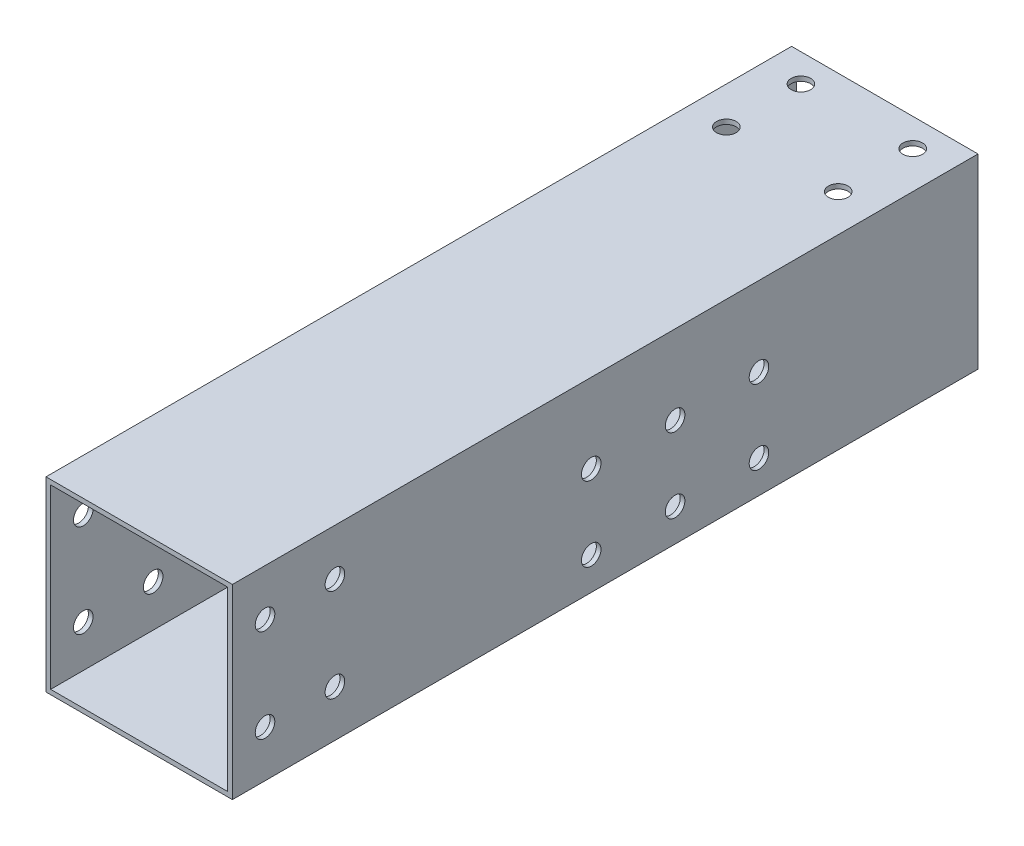
SolidWorks part; units mm, degrees
material "1060-H18 棒材(SS)"
ref_plane "前视基准面" through (0, 0, 0) normal (0, 0, 1) x (1, 0, 0)
ref_plane "上视基准面" through (0, 0, 0) normal (0, 1, 0) x (1, 0, 0)
ref_plane "右视基准面" through (0, 0, 0) normal (1, 0, 0) x (0, 0, -1)
other "Configuration Table"
sketch "草图1" plane through (0, 0, 0) normal (0, 0, 1) x (1, 0, 0)
  line L1 (0, 0) -> (40, 0)
  line L2 (0, 0) -> (0, 40)
  line L3 (0, 40) -> (40, 40)
  line L4 (40, 0) -> (40, 40)
  line L5 (1, 1) -> (39, 1)
  line L6 (1, 1) -> (1, 39)
  line L7 (1, 39) -> (39, 39)
  line L8 (39, 1) -> (39, 39)
  dimension "D1" = 40
  dimension "D2" = 40
  dimension "D3" = 1
  dimension "D4" = 1
  dimension "D5" = 1
  dimension "D6" = 1
extrude "凸台-拉伸1" add sketch "草图1" along normal blind 160
sketch "草图2" plane through (0, 0, 0) normal (0, -1, 0) x (1, 0, 0)
  circle A1 centre (8, 6) radius 2.1
  circle A2 centre (8, 6) radius 2.1
  circle A3 centre (32, 22) radius 2.1
  circle A4 centre (32, 22) radius 2.1
  circle A5 centre (8, 22) radius 2.1
  circle A6 centre (8, 22) radius 2.1
  circle A7 centre (72, -7) radius 2.1
  circle A8 centre (72, -7) radius 2.1 construction
  circle A9 centre (60, -7) radius 2.1
  circle A10 centre (60, -7) radius 2.1 construction
  circle A11 centre (-20, -7) radius 2.1
  circle A12 centre (-20, -7) radius 2.1 construction
  circle A13 centre (-32, -7) radius 2.1
  circle A14 centre (-32, -7) radius 2.1 construction
  circle A15 centre (32, 6) radius 2.1
  circle A16 centre (32, 6) radius 2.1
  dimension "D1" = 0
  dimension "D2" = 0
  dimension "D3" = 0
  dimension "D4" = 0
  dimension "D5" = 0
  dimension "D6" = 0
  dimension "D7" = 0
  dimension "D8" = 0
extrude "切除-拉伸1" cut sketch "草图2" against normal through all
sketch "草图4" plane through (0, 0, 0) normal (-1, 0, 0) x (0, 0, 1)
  circle A1 centre (138, 10) radius 2.1
  circle A2 centre (138, 10) radius 2.1
  circle A3 centre (153, 30) radius 2.1
  circle A4 centre (153, 30) radius 2.1
  circle A5 centre (153, 10) radius 2.1
  circle A6 centre (153, 10) radius 2.1
  circle A7 centre (192, 60) radius 2.1
  circle A8 centre (192, 60) radius 2.1 construction
  circle A9 centre (170, 60) radius 2.1
  circle A10 centre (170, 60) radius 2.1 construction
  circle A11 centre (170, 35) radius 2.1
  circle A12 centre (170, 35) radius 2.1 construction
  circle A13 centre (170, 5) radius 2.1
  circle A14 centre (170, 5) radius 2.1 construction
  circle A15 centre (192, -20) radius 2.1
  circle A16 centre (192, -20) radius 2.1 construction
  circle A17 centre (170, -20) radius 2.1
  circle A18 centre (170, -20) radius 2.1 construction
  circle A19 centre (138, 30) radius 2.1
  circle A20 centre (138, 30) radius 2.1
  circle A21 centre (192, 5) radius 2.1
  circle A22 centre (192, 5) radius 2.1 construction
  circle A23 centre (192, 35) radius 2.1
  circle A24 centre (192, 35) radius 2.1 construction
  circle A25 centre (83, 23) radius 2.1
  circle A26 centre (83, 23) radius 2.1
  circle A27 centre (74.9904, -30.6051) radius 1.6
  circle A28 centre (74.9904, -30.6051) radius 1.6 construction
  circle A29 centre (65, 7) radius 2.1
  circle A30 centre (65, 7) radius 2.1
  circle A31 centre (65, 23) radius 2.1
  circle A32 centre (65, 23) radius 2.1
  circle A33 centre (47, 7) radius 2.1
  circle A34 centre (47, 7) radius 2.1
  circle A35 centre (47, 23) radius 2.1
  circle A36 centre (47, 23) radius 2.1
  circle A37 centre (83, 7) radius 2.1
  circle A38 centre (83, 7) radius 2.1
  circle A39 centre (51.3301, -9.6244) radius 1.6
  circle A40 centre (51.3301, -9.6244) radius 1.6 construction
  circle A41 centre (59.9904, -4.6244) radius 1.6
  circle A42 centre (59.9904, -4.6244) radius 1.6 construction
  circle A43 centre (67.4904, -17.6147) radius 1.6
  circle A44 centre (67.4904, -17.6147) radius 1.6 construction
  circle A45 centre (58.8301, -22.6147) radius 1.6
  circle A46 centre (58.8301, -22.6147) radius 1.6 construction
  circle A47 centre (66.3301, -35.6051) radius 1.6
  circle A48 centre (66.3301, -35.6051) radius 1.6 construction
  dimension "D1" = 0
  dimension "D2" = 0
  dimension "D3" = 0
  dimension "D4" = 0
  dimension "D5" = 0
  dimension "D6" = 0
  dimension "D7" = 0
  dimension "D8" = 0
  dimension "D9" = 0
  dimension "D10" = 0
  dimension "D11" = 0
  dimension "D12" = 0
  dimension "D13" = 0
  dimension "D14" = 0
  dimension "D15" = 0
  dimension "D16" = 0
  dimension "D17" = 0
  dimension "D18" = 0
  dimension "D19" = 0
  dimension "D20" = 0
  dimension "D21" = 0
  dimension "D22" = 0
  dimension "D23" = 0
  dimension "D24" = 0
extrude "切除-拉伸2" cut sketch "草图4" against normal through all
